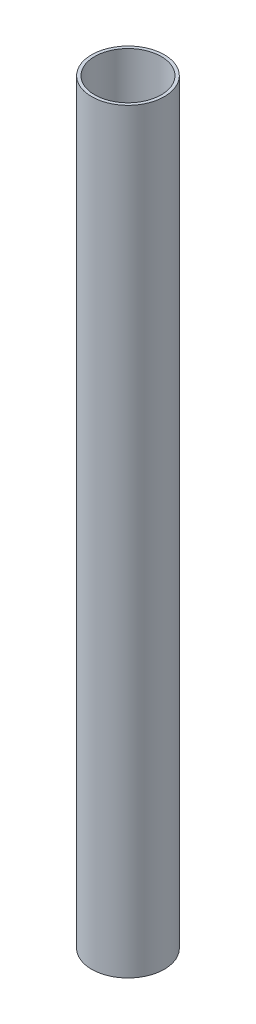
SolidWorks part; units mm, degrees
material "ASTM A36 Steel"
ref_plane "Front Plane" through (0, 0, 0) normal (0, 0, 1) x (1, 0, 0)
ref_plane "Top Plane" through (0, 0, 0) normal (0, 1, 0) x (1, 0, 0)
ref_plane "Right Plane" through (0, 0, 0) normal (1, 0, 0) x (0, 0, -1)
sketch "Sketch1" plane through (0, 0, 0) normal (0, 1, 0) x (1, 0, 0)
  circle A0 centre (0, 0) radius 84.1375
  circle A1 centre (0, 0) radius 77.0255
  dimension "D1" = 168.275
  dimension "D2" = 7.112
extrude "Boss-Extrude1" add sketch "Sketch1" along normal blind 1750
